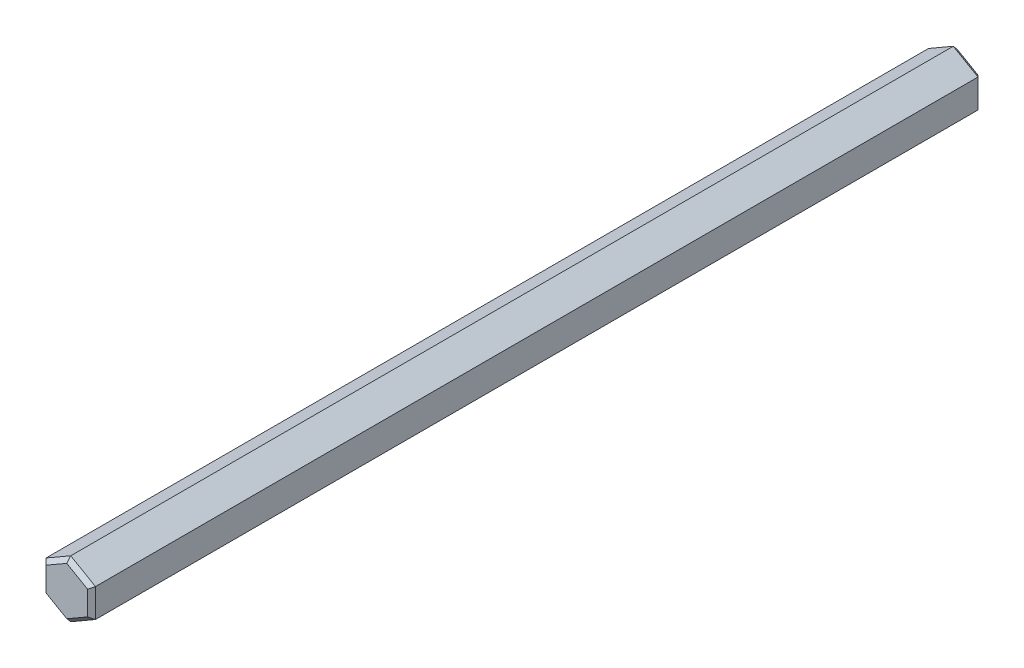
SolidWorks part; units mm, degrees
ref_plane "Front Plane" through (0, 0, 0) normal (0, 0, 1) x (1, 0, 0)
ref_plane "Top Plane" through (0, 0, 0) normal (0, 1, 0) x (1, 0, 0)
ref_plane "Right Plane" through (0, 0, 0) normal (1, 0, 0) x (0, 0, -1)
ref_plane "Plane1" through (0, 0, -45) normal (0, 0, -1) x (-1, 0, 0)
sketch "Sketch1" plane through (0, 0, -45) normal (0, 0, -1) x (-1, 0, 0)
  line L0 (0, -2.8868) -> (2.5, -1.4434)
  line L1 (2.5, -1.4434) -> (2.5, 1.4434)
  line L2 (2.5, 1.4434) -> (0, 2.8868)
  line L3 (0, 2.8868) -> (-2.5, 1.4434)
  line L4 (-2.5, 1.4434) -> (-2.5, -1.4434)
  line L5 (-2.5, -1.4434) -> (0, -2.8868)
extrude "Boss-Extrude1" add sketch "Sketch1" against normal blind 90
chamfer "Chamfer1" distance 0.4 angle 45 12 edges at (2.5, 0, 45) (1.25, 2.1651, 45) (1.25, -2.1651, 45) (-1.25, 2.1651, 45) (-1.25, -2.1651, 45) (-2.5, 0, 45) (1.25, 2.1651, -45) (2.5, 0, -45) (-1.25, 2.1651, -45) (1.25, -2.1651, -45) (-2.5, 0, -45) (-1.25, -2.1651, -45)
